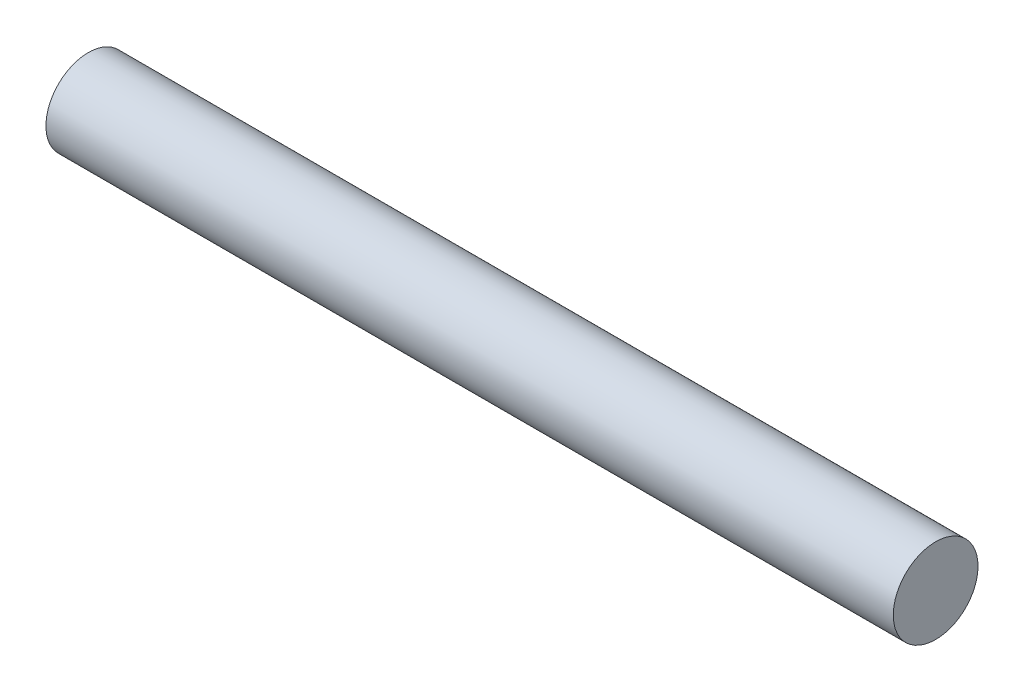
SolidWorks part; units mm, degrees
ref_plane "Front Plane" through (0, 0, 0) normal (0, 0, 1) x (1, 0, 0)
ref_plane "Top Plane" through (0, 0, 0) normal (0, 1, 0) x (1, 0, 0)
ref_plane "Right Plane" through (0, 0, 0) normal (1, 0, 0) x (0, 0, -1)
sketch "Sketch1" plane through (0, 0, 0) normal (1, 0, 0) x (0, 0, -1)
  circle A0 centre (0, 0) radius 2.5
extrude "Boss-Extrude1" add sketch "Sketch1" along normal mid plane 50
